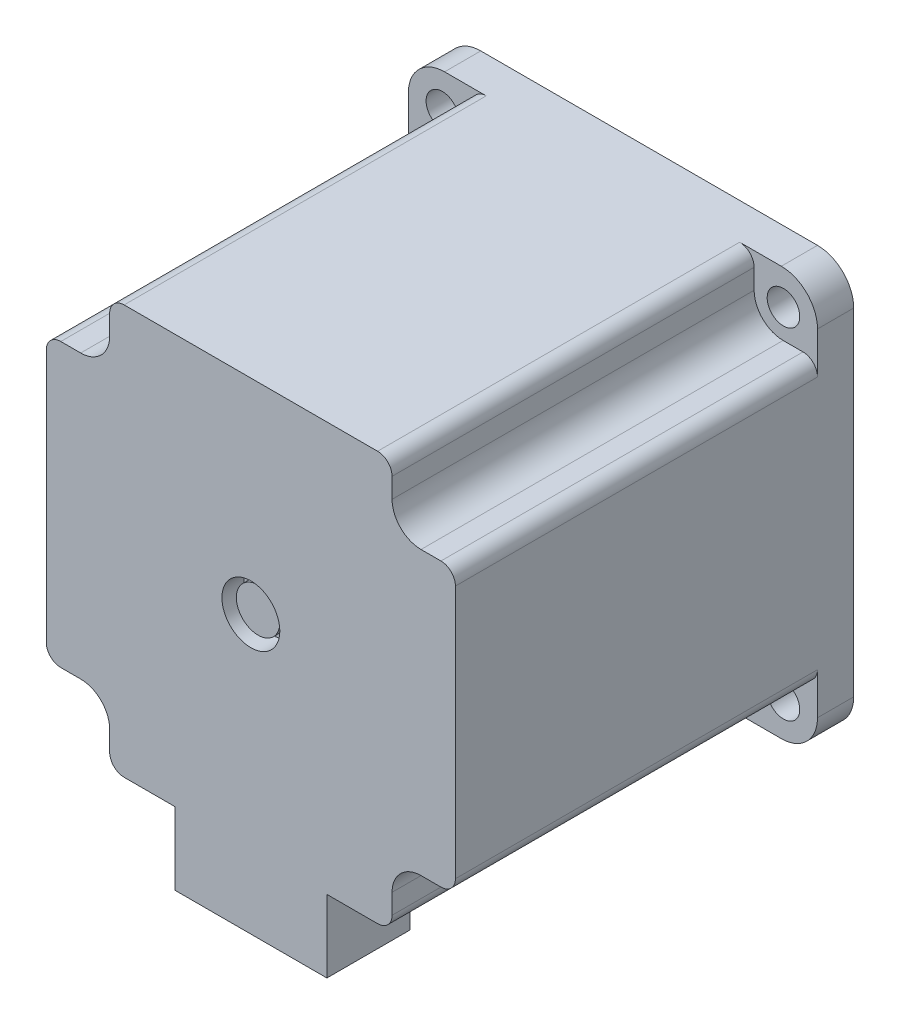
SolidWorks part; units mm, degrees
material "SKD11淬火HRC56-60"
ref_plane "前基準面" through (0, 0, 0) normal (0, 0, 1) x (1, 0, 0)
ref_plane "上基準面" through (0, 0, 0) normal (0, 1, 0) x (1, 0, 0)
ref_plane "右基準面" through (0, 0, 0) normal (1, 0, 0) x (0, 0, -1)
sketch "草图1" plane through (0, 0, 0) normal (0, 0, 1) x (1, 0, 0)
  line L1 (0, 0) -> (56.5, 0)
  line L2 (0, 0) -> (0, 56.5)
  line L3 (0, 56.5) -> (56.5, 56.5)
  line L4 (56.5, 0) -> (56.5, 56.5)
  dimension "D1" = 56.5
extrude "凸台-拉伸1" add sketch "草图1" along normal blind 55
fillet "圆角1" radius 5 4 edges at (56.5, 0, 27.5) (0, 0, 27.5) (0, 56.5, 27.5) (56.5, 56.5, 27.5)
sketch "草图2" plane through (0, 0, 55) normal (0, 0, 1) x (1, 0, 0)
  line L0 (28.25, 56.5) -> (28.25, 0) construction
  line L1 (-19.1874, 65.2751) -> (8.75, 65.2751)
  line L2 (-19.1874, 65.2751) -> (-19.1874, 47.75)
  line L3 (-19.1874, 47.75) -> (8.75, 47.75)
  line L4 (8.75, 65.2751) -> (8.75, 47.75)
  line L5 (51.5, 56.5) -> (5, 56.5) construction
  line L6 (5, 0) -> (51.5, 0) construction
  line L7 (0, 28.25) -> (56.5, 28.25) construction
  line L8 (0, 51.5) -> (0, 5) construction
  line L9 (56.5, 5) -> (56.5, 51.5) construction
  line L10 (47.75, 65.2751) -> (47.75, 47.75)
  line L11 (75.6874, 47.75) -> (47.75, 47.75)
  line L12 (75.6874, 65.2751) -> (75.6874, 47.75)
  line L13 (75.6874, 65.2751) -> (47.75, 65.2751)
  line L14 (75.6874, -8.7751) -> (47.75, -8.7751)
  line L15 (75.6874, -8.7751) -> (75.6874, 8.75)
  line L16 (75.6874, 8.75) -> (47.75, 8.75)
  line L17 (47.75, -8.7751) -> (47.75, 8.75)
  line L18 (8.75, -8.7751) -> (8.75, 8.75)
  line L19 (-19.1874, 8.75) -> (8.75, 8.75)
  line L20 (-19.1874, -8.7751) -> (-19.1874, 8.75)
  line L21 (-19.1874, -8.7751) -> (8.75, -8.7751)
  dimension "D1" = 39
  dimension "D2" = 39
extrude "切除-拉伸1" cut sketch "草图2" against normal blind 50
fillet "圆角2" radius 4 4 edges at (8.75, 8.75, 30) (47.75, 8.75, 30) (47.75, 47.75, 30) (8.75, 47.75, 30)
fillet "圆角3" radius 2 8 edges at (0, 8.75, 30) (8.75, 0, 30) (47.75, 0, 30) (56.5, 8.75, 30) (56.5, 47.75, 30) (47.75, 56.5, 30) (8.75, 56.5, 30) (0, 47.75, 30)
sketch "草图3" plane through (0, 0, 0) normal (0, 0, -1) x (-1, 0, 0)
  line L0 (-56.5, 28.25) -> (0, 28.25) construction
  line L1 (-56.5, 5) -> (-56.5, 51.5) construction
  line L2 (0, 51.5) -> (0, 5) construction
  circle A0 centre (-28.25, 28.25) radius 19
  dimension "D1" = 38
extrude "凸台-拉伸2" add sketch "草图3" along normal blind 1.5
sketch "草图4" plane through (0, 0, 55) normal (0, 0, 1) x (1, 0, 0)
  line L0 (56.5, 28.25) -> (0, 28.25) construction
  line L1 (56.5, 10.75) -> (56.5, 45.75) construction
  line L2 (0, 45.75) -> (0, 10.75) construction
  circle A0 centre (28.25, 28.25) radius 4
  dimension "D1" = 8
extrude "切除-拉伸2" cut sketch "草图4" against normal blind 3
sketch "草图5" plane through (0, 0, 52) normal (0, 0, 1) x (1, 0, 0)
  circle A0 centre (28.25, 28.25) radius 3
  dimension "D1" = 6
extrude "凸台-拉伸3" add sketch "草图5" along normal blind 2
sketch "草图6" plane through (0, 0, -1.5) normal (0, 0, -1) x (-1, 0, 0)
  circle A0 centre (-28.25, 28.25) radius 3.175
  dimension "D1" = 6.35
extrude "凸台-拉伸4" add sketch "草图6" along normal blind 21
sketch "草图7" plane through (0, 0, 0) normal (0, 0, -1) x (-1, 0, 0)
  line L0 (-56.5, 28.25) -> (0, 28.25) construction
  line L1 (-56.5, 5) -> (-56.5, 51.5) construction
  line L2 (0, 51.5) -> (0, 5) construction
  line L3 (-28.25, 56.5) -> (-28.25, 0) construction
  line L4 (-51.5, 56.5) -> (-5, 56.5) construction
  line L5 (-5, 0) -> (-51.5, 0) construction
  circle A0 centre (-51.8, 4.75) radius 2.25
  circle A1 centre (-4.7, 4.75) radius 2.25
  circle A2 centre (-4.7, 51.75) radius 2.25
  circle A3 centre (-51.8, 51.75) radius 2.25
  dimension "D1" = 4.5
  dimension "D2" = 47
  dimension "D3" = 47.1
extrude "切除-拉伸3" cut sketch "草图7" against normal blind 21
sketch "草图8" plane through (0, 0, 0) normal (0, -1, 0) x (1, 0, 0)
  line L0 (10.75, 55) -> (45.75, 55) construction
  line L1 (17.75, 55) -> (38.75, 55)
  line L2 (17.75, 55) -> (17.75, 43.5)
  line L3 (17.75, 43.5) -> (38.75, 43.5)
  line L4 (38.75, 55) -> (38.75, 43.5)
  line L5 (28.25, 55) -> (28.25, 42.9487) construction
  dimension "D1" = 21
  dimension "D2" = 11.5
extrude "凸台-拉伸5" add sketch "草图8" along normal blind 10
sketch "草图9" plane through (0, -10, 0) normal (0, -1, 0) x (1, 0, 0)
  line L0 (28.25, 43.5) -> (28.25, 55) construction
  line L1 (34.25, 47.5) -> (22.25, 47.5)
  line L2 (34.25, 47.5) -> (34.25, 44.5)
  line L3 (34.25, 44.5) -> (22.25, 44.5)
  line L4 (22.25, 47.5) -> (22.25, 44.5)
  line L5 (17.75, 43.5) -> (38.75, 43.5) construction
  line L6 (38.75, 55) -> (17.75, 55) construction
  dimension "D1" = 3
  dimension "D2" = 1
  dimension "D3" = 12
extrude "切除-拉伸4" cut sketch "草图9" against normal blind 5
